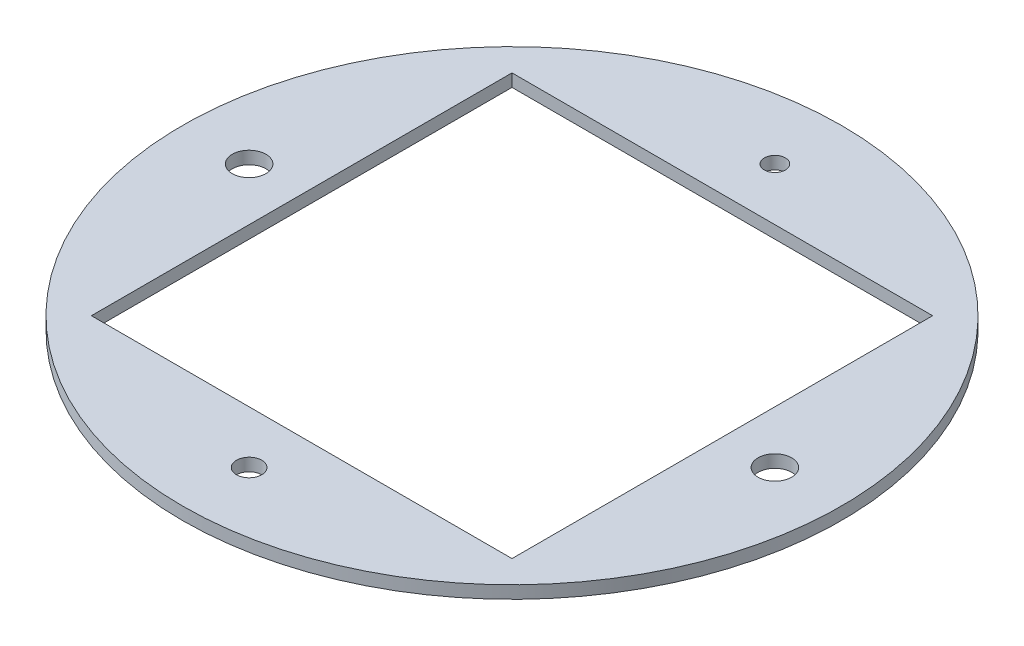
SolidWorks part; units mm, degrees
material "1060 Alloy"
ref_plane "Front Plane" through (0, 0, 0) normal (0, 0, 1) x (1, 0, 0)
ref_plane "Top Plane" through (0, 0, 0) normal (0, 1, 0) x (1, 0, 0)
ref_plane "Right Plane" through (0, 0, 0) normal (1, 0, 0) x (0, 0, -1)
sketch "Sketch1" plane through (0, 0, 0) normal (0, 1, 0) x (1, 0, 0)
  line L1 (50, -50) -> (-50, -50)
  line L2 (50, -50) -> (50, 50)
  line L3 (50, 50) -> (-50, 50)
  line L4 (-50, -50) -> (-50, 50)
  line L5 (50, -50) -> (-50, 50) construction
  line L6 (50, 50) -> (-50, -50) construction
  circle A0 centre (0, 0) radius 78.35
  circle A1 centre (-62.5, 0) radius 4
  circle A2 centre (0, 0) radius 62.5 construction
  circle A3 centre (0, -62.5) radius 3
  circle A4 centre (0, 62.5) radius 2.5
  circle A5 centre (62.5, 0) radius 4
  dimension "D1" = 156.7
  dimension "D2" = 125
  dimension "D3" = 8
  dimension "D4" = 8
  dimension "D5" = 5
  dimension "D6" = 6
  dimension "D7" = 100
  dimension "D8" = 100
extrude "Boss-Extrude1" add sketch "Sketch1" along normal blind 3
